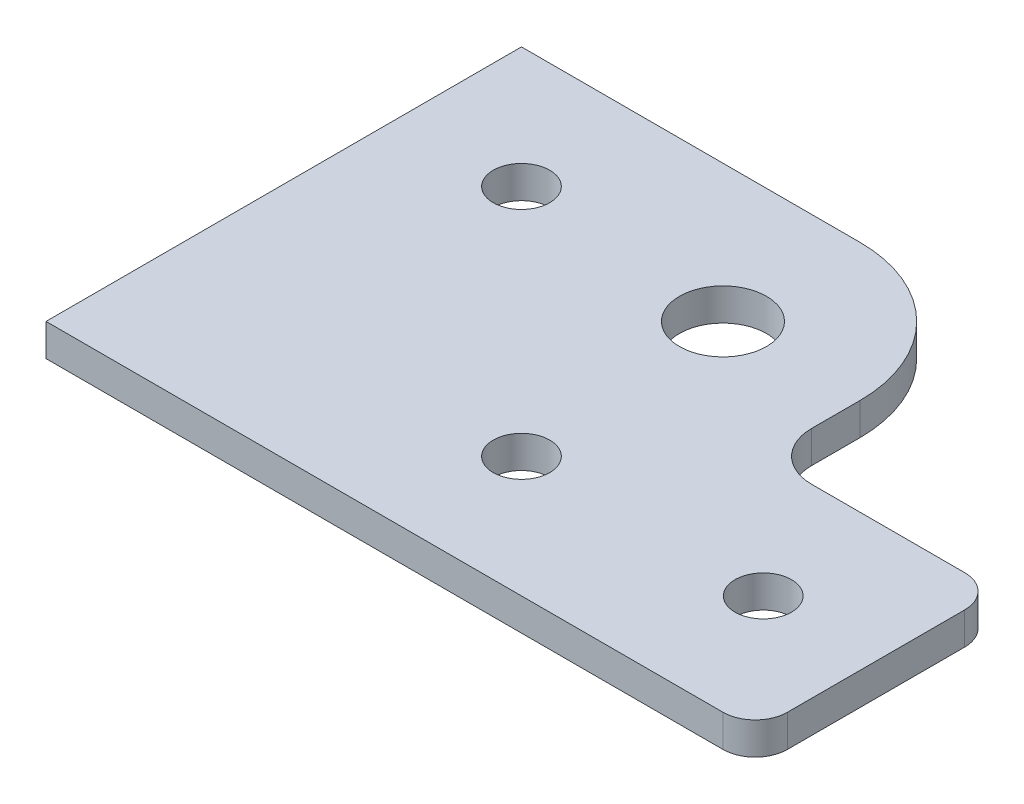
SolidWorks part; units mm, degrees
ref_plane "前视基准面" through (0, 0, 0) normal (0, 0, 1) x (1, 0, 0)
ref_plane "上视基准面" through (0, 0, 0) normal (0, 1, 0) x (1, 0, 0)
ref_plane "右视基准面" through (0, 0, 0) normal (1, 0, 0) x (0, 0, -1)
other "Configuration Table"
sketch "草图1" plane through (0, 0, 0) normal (0, 1, 0) x (1, 0, 0)
  line L0 (0, 0) -> (42, 0)
  line L1 (44, 2) -> (44, 13)
  line L2 (42, 15) -> (29.5, 15)
  line L3 (15, 15) -> (15, 27)
  line L4 (15, 27) -> (0, 27)
  line L5 (0, 27) -> (0, 0)
  line L6 (7.5, 34.1241) -> (7.5, -10.2397) construction
  line L7 (45.5156, 7.5) -> (-18.2044, 7.5) construction
  line L8 (-17.173, 22) -> (17.9369, 22) construction
  line L9 (15, 15) -> (15, -10.2397) construction
  line L10 (21, 56.8709) -> (21, -35.1811) construction
  line L12 (25.7658, 27) -> (15, 27)
  line L13 (-25.7738, 21) -> (35.8148, 21) construction
  line L14 (15, 27) -> (27.7658, 27)
  line L15 (29.5, 21) -> (29.5, 15)
  line L16 (0, 27) -> (21, 29.5)
  circle A0 centre (7.5, 22) radius 1.75
  circle A1 centre (22, 7.5) radius 1.75
  circle A2 centre (37, 7.5) radius 1.75
  arc A4 (42, 0) -> (44, 2) centre (42, 2) ccw
  arc A5 (44, 13) -> (42, 15) centre (42, 13) ccw
  circle A8 centre (21, 21) radius 5
  circle A9 centre (21, 21) radius 8.5
  point P30 (44, 0)
  point P33 (44, 15)
  dimension "D5" = 3.5
  dimension "D7" = 3.5
  dimension "D8" = 3.5
  dimension "D10" = 7
  dimension "D14" = 2
  dimension "D16" = 10
  dimension "D17" = 17
  dimension "D1" = 15
  dimension "D2" = 15
  dimension "D3" = 15
  dimension "D4" = 12
  dimension "D6" = 5
  dimension "D9" = 7
  dimension "D11" = 21
  dimension "D13" = 6
extrude "凸台-拉伸1" add sketch "草图1" along normal blind 2
fillet "圆角1" radius 3 1 edges at (29.5, 1, -15)
sketch "草图2" plane through (0, 2, 0) normal (0, 1, 0) x (1, 0, 0)
  circle A1 centre (21, 21) radius 5 construction
  circle A2 centre (21, 21) radius 5
  circle A3 centre (21, 21) radius 2.7
  dimension "D1" = 5.4
extrude "凸台-拉伸2" add sketch "草图2" against normal blind 2
sketch "草图3" plane through (0, 2, 0) normal (0, 1, 0) x (1, 0, 0)
  line L0 (21, 29.5) -> (0, 29.5)
  line L1 (0, 29.5) -> (0, 27)
  line L2 (0, 27) -> (21, 29.5)
extrude "凸台-拉伸3" add sketch "草图3" against normal blind 2
ref_plane "基准面1" through (0, 0, -21) normal (0, 0, 1) x (1, 0, 0)
